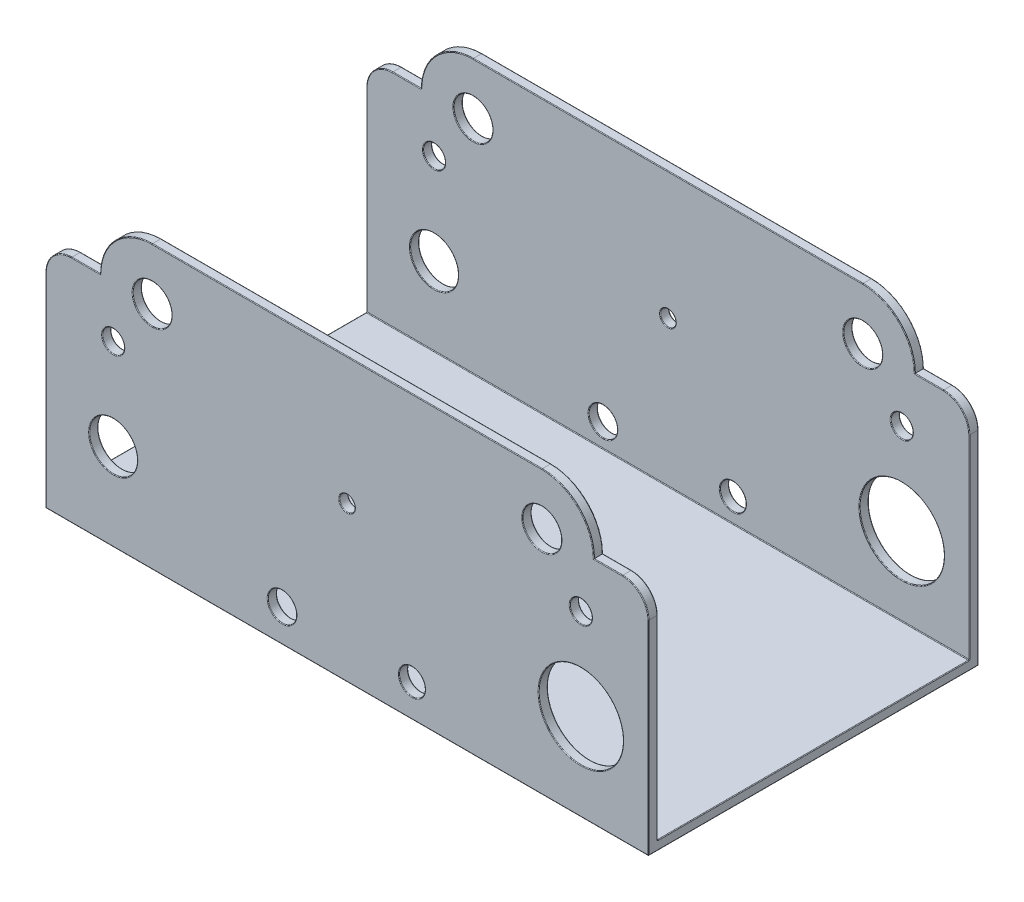
SolidWorks part; units mm, degrees
ref_plane "前视基准面" through (0, 0, 0) normal (0, 0, 1) x (1, 0, 0)
ref_plane "上视基准面" through (0, 0, 0) normal (0, 1, 0) x (1, 0, 0)
ref_plane "右视基准面" through (0, 0, 0) normal (1, 0, 0) x (0, 0, -1)
sketch "草图1" plane through (0, 0, 0) normal (0, 1, 0) x (1, 0, 0)
  line L0 (-137.7361, 0) -> (189.6108, 0) construction
  line L1 (0, 139.5635) -> (0, -107.4704) construction
  line L2 (-232, -127) -> (232, -127)
  line L3 (-232, -127) -> (-232, 127)
  line L4 (232, -127) -> (232, 127)
  line L5 (-232, 127) -> (232, 127)
  line L6 (232, 0) -> (-232, 0) construction
  line L7 (0, -127) -> (0, 127) construction
  point P5 (0, 0)
extrude "凸台-拉伸1" add sketch "草图1" along normal blind 7
ref_plane "机箱底部参考面" through (0, 7, 0) normal (0, 1, 0) x (1, 0, 0)
sketch "草图2" plane through (0, 7, 0) normal (0, 1, 0) x (1, 0, 0)
  line L0 (-187.885, 0) -> (26.3535, 0) construction
  line L1 (0, 109.464) -> (0, -80.0114) construction
  line L2 (232, 127) -> (-232, 127) construction
  line L3 (-232, 127) -> (232, 127)
  line L4 (232, -127) -> (232, 127) construction
  line L5 (-232, 127) -> (-232, 120)
  line L6 (-232, 127) -> (-232, -127) construction
  line L7 (-232, 120) -> (232, 120)
  line L8 (232, 120) -> (232, 127)
  line L9 (232, -120) -> (232, -127)
  line L10 (-232, -120) -> (232, -120)
  line L11 (-232, -127) -> (-232, -120)
  line L12 (-232, -127) -> (232, -127)
  point P7 (0, 127)
extrude "凸台-拉伸2" add sketch "草图2" along normal blind 210 contours L7 L8 L3 L5 | L11 L12 L9 L10
ref_plane "主驱动轴高度面" through (0, 67, 0) normal (0, 1, 0) x (1, 0, 0)
ref_plane "前驱动轮轴位置" through (-180, 0, 0) normal (-1, 0, 0) x (0, 0, 1)
ref_plane "后驱动轮轴位置" through (180, 0, 0) normal (1, 0, 0) x (0, 0, -1)
ref_plane "前摇臂轴位置" through (-150, 0, 0) normal (-1, 0, 0) x (0, 0, 1)
ref_plane "后摇臂轴位置" through (150, 0, 0) normal (1, 0, 0) x (0, 0, -1)
ref_plane "驱动摇臂中间轴高度" through (0, 137, 0) normal (0, 1, 0) x (1, 0, 0)
ref_plane "摇臂轴高度" through (0, 177, 0) normal (0, 1, 0) x (1, 0, 0)
ref_plane "左箱壁外侧" through (0, 0, 127) normal (0, 0, 1) x (1, 0, 0)
ref_plane "右箱壁外侧" through (0, 0, -127) normal (0, 0, -1) x (-1, 0, 0)
sketch "草图4" plane through (0, 0, 127) normal (0, 0, 1) x (1, 0, 0)
  line L0 (-180, 119.35) -> (-180, -119.35) construction
  line L1 (132, 67) -> (-132, 67) construction
  line L2 (132, 137) -> (-132, 137) construction
  line L3 (-150, 119.35) -> (-150, -119.35) construction
  line L4 (132, 177) -> (-132, 177) construction
  line L5 (180, -119.35) -> (180, 119.35) construction
  line L6 (150, -119.35) -> (150, 119.35) construction
  circle A0 centre (-180, 67) radius 18.5
  circle A1 centre (-180, 137) radius 8.5
  circle A2 centre (180, 137) radius 8.5
  circle A3 centre (-150, 177) radius 15
  circle A4 centre (150, 177) radius 15
  circle A5 centre (180, 67) radius 32.5
  point P0 (-180, 67)
  point P1 (-180, 137)
  point P6 (-150, 177)
  point P9 (180, 67)
  point P14 (180, 137)
  point P17 (150, 177)
  point P32 (0, 0)
  point P33 (0, 0)
extrude "切除-拉伸1" cut sketch "草图4" against normal through all
sketch "草图6" plane through (0, 0, 127) normal (0, 0, 1) x (1, 0, 0)
  line L0 (-96.3485, 0) -> (48.7137, 0) construction
  line L2 (0, 51.5411) -> (0, -34.3465) construction
  line L3 (-134.1119, 25.075) -> (85.2304, 25.075) construction
  circle A0 centre (-50, 25.075) radius 11
  circle A1 centre (50, 25.075) radius 10
  circle A2 centre (0, 119) radius 6
  point P8 (50, 25.075)
  point P9 (-50, 25.075)
  point P11 (0, 119)
extrude "切除-拉伸2" cut sketch "草图6" against normal through all
sketch "草图7" plane through (0, 0, -127) normal (0, 0, -1) x (-1, 0, 0)
  line L0 (0, 99.6828) -> (0, 41.7932) construction
  line L1 (-232, 217) -> (-232, 177)
  line L3 (-232, 217) -> (-150, 217)
  line L5 (-190, 177) -> (-232, 177)
  line L6 (190, 177) -> (232, 177)
  line L7 (232, 217) -> (150, 217)
  line L8 (232, 217) -> (232, 177)
  arc A0 (-150, 217) -> (-190, 177) centre (-150, 177) ccw
  arc A1 (150, 217) -> (190, 177) centre (150, 177) cw
  point P6 (0, 0)
extrude "切除-拉伸3" cut sketch "草图7" against normal through all
fillet "圆角1" radius 20 1 edges at (232, 177, 123.5)
fillet "圆角2" radius 20 1 edges at (232, 177, -123.5)
fillet "圆角3" radius 20 1 edges at (-232, 177, 123.5)
fillet "圆角4" radius 20 1 edges at (-232, 177, -123.5)
fillet "圆角5" radius 0.5 80 edges at (232, 0, 0) (-232, 0, 0) (232, 7, 0) (-232, 7, 0) (-178.2843, 205.2843, 127) (0, 217, 127) (178.2843, 205.2843, 127) (201, 177, 127) (226.1421, 171.1421, 127) (232, 78.5, 127) (0, 0, 127) (-232, 78.5, 127) (-226.1421, 171.1421, 127) (-201, 177, 127) (-161.5, 67, 127) (-171.5, 137, 127) (188.5, 137, 127) (-135, 177, 127) (165, 177, 127) (212.5, 67, 127) (-39, 25.075, 127) (6, 119, 127) (60, 25.075, 127) (-198.5, 67, 120) (-188.5, 137, 120) (171.5, 137, 120) (-165, 177, 120) (135, 177, 120) (147.5, 67, 120) (-61, 25.075, 120) (-6, 119, 120) (40, 25.075, 120) (0, 7, 120) (232, 82, 120) (226.1421, 171.1421, 120) (201, 177, 120) (178.2843, 205.2843, 120) (0, 217, 120) (-178.2843, 205.2843, 120) (-201, 177, 120) (-226.1421, 171.1421, 120) (-232, 82, 120) (-178.2843, 205.2843, -120) (0, 217, -120) (178.2843, 205.2843, -120) (201, 177, -120) (226.1421, 171.1421, -120) (232, 82, -120) (0, 7, -120) (-232, 82, -120) (-226.1421, 171.1421, -120) (-201, 177, -120) (-198.5, 67, -120) (-188.5, 137, -120) (171.5, 137, -120) (-165, 177, -120) (135, 177, -120) (147.5, 67, -120) (-61, 25.075, -120) (-6, 119, -120) (40, 25.075, -120) (0, 0, -127) (232, 78.5, -127) (226.1421, 171.1421, -127) (201, 177, -127) (178.2843, 205.2843, -127) (0, 217, -127) (-178.2843, 205.2843, -127) (-201, 177, -127) (-226.1421, 171.1421, -127) (-232, 78.5, -127) (-161.5, 67, -127) (-171.5, 137, -127) (188.5, 137, -127) (-135, 177, -127) (165, 177, -127) (212.5, 67, -127) (-39, 25.075, -127) (6, 119, -127) (60, 25.075, -127)
